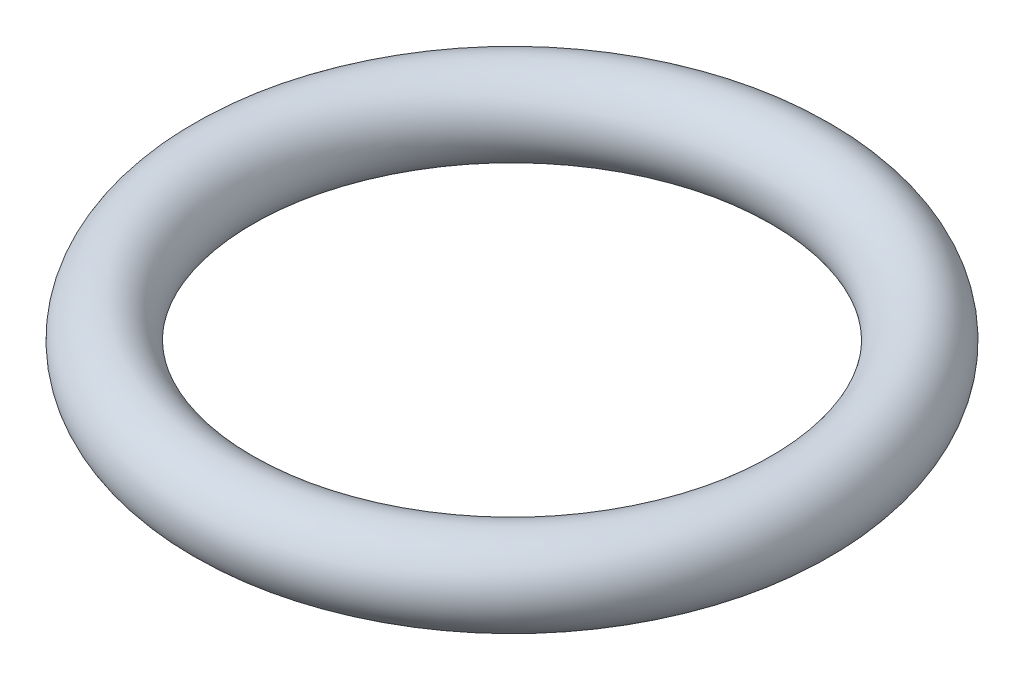
SolidWorks part; units mm, degrees
ref_plane "Front Plane" through (0, 0, 0) normal (0, 0, 1) x (1, 0, 0)
ref_plane "Top Plane" through (0, 0, 0) normal (0, 1, 0) x (1, 0, 0)
ref_plane "Right Plane" through (0, 0, 0) normal (1, 0, 0) x (0, 0, -1)
sketch "Sketch2" plane through (0, 0, 0) normal (0, 0, 1) x (1, 0, 0)
  line L0 (0, 0) -> (0, 3.8497) construction
  circle A0 centre (5.25, 0) radius 0.75
  dimension "D1" = 1.5
  dimension "D2" = 5.25
revolve "Revolve1" add sketch "Sketch2" angle 360 about L0
